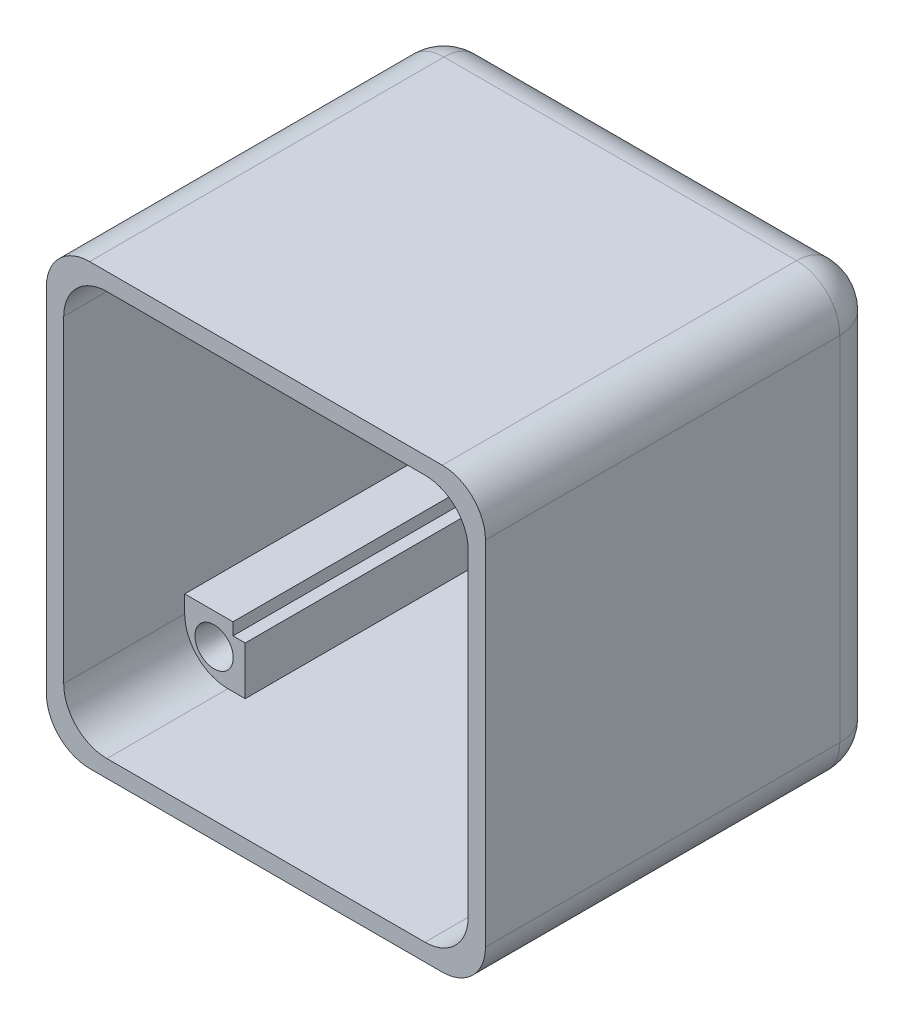
SolidWorks part; units mm, degrees
material "ABS"
ref_plane "X-Y Datum" through (0, 0, 0) normal (0, 0, 1) x (1, 0, 0)
ref_plane "X-Z Datum" through (0, 0, 0) normal (0, 1, 0) x (1, 0, 0)
ref_plane "Y-Z Datum" through (0, 0, 0) normal (1, 0, 0) x (0, 0, -1)
sketch "Sketch1" plane through (0, 0, 0) normal (0, 0, 1) x (1, 0, 0)
  line L0 (-32.258, -32.258) -> (-32.258, -11.938)
  line L1 (32.258, 32.258) -> (-32.258, 32.258)
  line L2 (32.258, 32.258) -> (32.258, -32.258)
  line L3 (32.258, -32.258) -> (-32.258, -32.258)
  line L5 (32.258, 32.258) -> (-32.258, -32.258) construction
  line L6 (32.258, -32.258) -> (-32.258, 32.258) construction
  line L7 (55.1739, 0) -> (-55.1739, 0) construction
  line L8 (-32.258, 32.258) -> (-32.258, 11.938)
  line L9 (-32.258, 11.938) -> (-32.258, -11.938)
  arc A0 (-32.258, -11.938) -> (-32.258, 11.938) centre (-9.8383, 0) cw construction
  point P0 (0, 0)
  dimension "D2" = 25.4
  dimension "D1" = 64.516
  dimension "D3" = 20.32
extrude "Boss-Extrude1" add sketch "Sketch1" along normal mid plane 58.42
shell "Shell1" thickness 2.54
fillet "Fillet1" radius 6.35 12 edges at (32.258, 0, -29.21) (0, 32.258, -29.21) (-32.258, 0, -29.21) (0, -32.258, -29.21) (32.258, 32.258, 0) (32.258, -32.258, 0) (-32.258, -32.258, 0) (-32.258, 32.258, 0) (29.718, 29.718, 1.27) (29.718, -29.718, 1.27) (-29.718, -29.718, 1.27) (-29.718, 29.718, 1.27)
sketch "Sketch2" plane through (0, 0, -26.67) normal (0, 0, 1) x (1, 0, 0)
  line L0 (55.1739, 0) -> (-55.1739, 0) construction
  line L1 (-23.368, 29.718) -> (-20.828, 29.718)
  line L8 (-29.718, -20.828) -> (-20.828, -20.828)
  line L9 (-29.718, 20.828) -> (-29.718, 23.368)
  line L15 (-20.828, -29.718) -> (-20.828, -20.828)
  line L16 (29.718, -23.368) -> (29.718, 23.368)
  line L17 (23.368, 29.718) -> (-23.368, 29.718)
  line L18 (-29.718, 23.368) -> (-29.718, -23.368)
  line L20 (-23.368, -29.718) -> (23.368, -29.718)
  line L25 (-23.368, -29.718) -> (-20.828, -29.718)
  line L26 (-20.828, 29.718) -> (-20.828, 20.828)
  line L27 (-29.718, 20.828) -> (-20.828, 20.828)
  line L28 (0, -43.0151) -> (0, 43.0151) construction
  line L29 (29.718, 20.828) -> (20.828, 20.828)
  line L30 (20.828, 29.718) -> (20.828, 20.828)
  line L31 (23.368, -29.718) -> (20.828, -29.718)
  line L32 (29.718, -20.828) -> (29.718, -23.368)
  line L33 (20.828, -29.718) -> (20.828, -20.828)
  line L34 (29.718, 20.828) -> (29.718, 23.368)
  line L35 (29.718, -20.828) -> (20.828, -20.828)
  line L36 (23.368, 29.718) -> (20.828, 29.718)
  arc A9 (-29.718, 23.368) -> (-23.368, 29.718) centre (-23.368, 23.368) cw
  arc A10 (29.718, 23.368) -> (23.368, 29.718) centre (23.368, 23.368) ccw
  arc A19 (-23.368, 29.718) -> (-29.718, 23.368) centre (-23.368, 23.368) ccw
  arc A21 (-29.718, -23.368) -> (-23.368, -29.718) centre (-23.368, -23.368) ccw
  arc A22 (23.368, -29.718) -> (29.718, -23.368) centre (23.368, -23.368) ccw
  arc A26 (-29.718, -23.368) -> (-23.368, -29.718) centre (-23.368, -23.368) ccw
  arc A27 (29.718, -23.368) -> (23.368, -29.718) centre (23.368, -23.368) cw
  arc A28 (29.718, 23.368) -> (23.368, 29.718) centre (23.368, 23.368) ccw
  line M7 (-23.368, -29.718) -> (23.368, -29.718)
  line M12 (-29.718, 23.368) -> (-29.718, -23.368)
  arc M22 (-29.718, -23.368) -> (-23.368, -29.718) centre (-23.368, -23.368) ccw
  dimension "D2" = 8.89
  dimension "D1" = 0
extrude "Boss-Extrude2" add sketch "Sketch2" along normal blind 38.1 contours L15 L8 M7 M12 M22 | A9 L1 L26 L27 L9 | A28 L36 L30 L29 L34 | A27 L31 L33 L35 L32
sketch "Sketch4" [suppressed] plane through (0, 0, 11.43) normal (0, 0, 1) x (1, 0, 0)
  line L0 (-20.828, -29.718) -> (-20.828, -20.828) construction
  line L1 (-20.828, -22.5) -> (-20.828, -20.828)
  line L2 (-20.828, -20.828) -> (-29.718, -20.828) construction
  line L3 (-20.828, -20.828) -> (-22.648, -20.828)
  line L4 (-22.648, -18) -> (-22.648, -22.5) construction
  line L5 (-22.648, -20.828) -> (-22.648, -22.5)
  line L6 (-22.648, -22.5) -> (22.352, -22.5) construction
  line L7 (-22.648, -22.5) -> (-20.828, -22.5)
  line L8 (-22.648, 22.5) -> (-22.648, 17) construction
  line L9 (-22.648, 22.5) -> (-22.648, 20.828)
  line L10 (-22.648, 22.5) -> (22.352, 22.5) construction
  line L11 (-22.648, 22.5) -> (-20.828, 22.5)
  line L12 (-20.828, 20.828) -> (-20.828, 29.718) construction
  line L13 (-20.828, 20.828) -> (-20.828, 22.5)
  line L14 (-29.718, 20.828) -> (-20.828, 20.828) construction
  line L15 (-22.648, 20.828) -> (-20.828, 20.828)
  line L16 (20.828, 20.828) -> (29.718, 20.828) construction
  line L17 (22.352, 22.5) -> (22.352, 11.7) construction
  line L18 (20.828, 29.718) -> (20.828, 20.828) construction
  line L19 (20.828, 20.828) -> (22.352, 20.828)
  line L20 (22.352, 22.5) -> (22.352, 20.828)
  line L21 (20.828, 22.5) -> (20.828, 20.828)
  line L22 (22.352, -13.5) -> (22.352, -22.5) construction
  line L23 (20.828, -20.828) -> (20.828, -29.718) construction
  line L24 (29.718, -20.828) -> (20.828, -20.828) construction
  line L25 (-22.648, -22.5) -> (-20.828, -22.5)
  line L26 (22.352, -20.828) -> (22.352, -22.5)
  line L27 (20.828, -20.828) -> (20.828, -22.5)
  line L28 (22.352, -20.828) -> (20.828, -20.828)
  line L29 (20.828, -22.5) -> (22.352, -22.5)
  line L30 (20.828, 22.5) -> (22.352, 22.5)
extrude "Cut-Extrude4" [suppressed] cut sketch "Sketch4" against normal up to surface (38.1 mm away)
sketch "Sketch3" plane through (0, 0, 11.43) normal (0, 0, 1) x (1, 0, 0)
  line L0 (-25.908, -32.258) -> (25.908, -32.258) construction
  line L4 (-32.258, 25.908) -> (-32.258, -25.908) construction
  line L5 (55.1739, 0) -> (-55.1739, 0) construction
  line L6 (0, -43.0151) -> (0, 43.0151) construction
  circle A0 centre (-25.4, -25.4) radius 2.8067
  circle A1 centre (-25.4, 25.4) radius 2.8067
  circle A2 centre (25.4, 25.4) radius 2.8067
  circle A3 centre (25.4, -25.4) radius 2.8067
  dimension "D1" = 6.858
  dimension "D3" = 5.6134
  dimension "D2" = 6.858
extrude "Cut-Extrude1" cut sketch "Sketch3" against normal blind 4.7 draft 8
sketch "Sketch5" plane through (0, 0, 11.43) normal (0, 0, 1) x (1, 0, 0)
  line L1 (-22.627, -22.627) -> (22.627, -22.627)
  line L2 (-22.627, -22.627) -> (-22.627, 22.627)
  line L3 (-22.627, 22.627) -> (22.627, 22.627)
  line L4 (22.627, -22.627) -> (22.627, 22.627)
  line L5 (-22.627, -22.627) -> (22.627, 22.627) construction
  line L6 (-22.627, 22.627) -> (22.627, -22.627) construction
  point P0 (0, 0)
extrude "Cut-Extrude5" cut sketch "Sketch5" against normal up to surface (38.1 mm away) up to face at (0, 0, -26.67)
